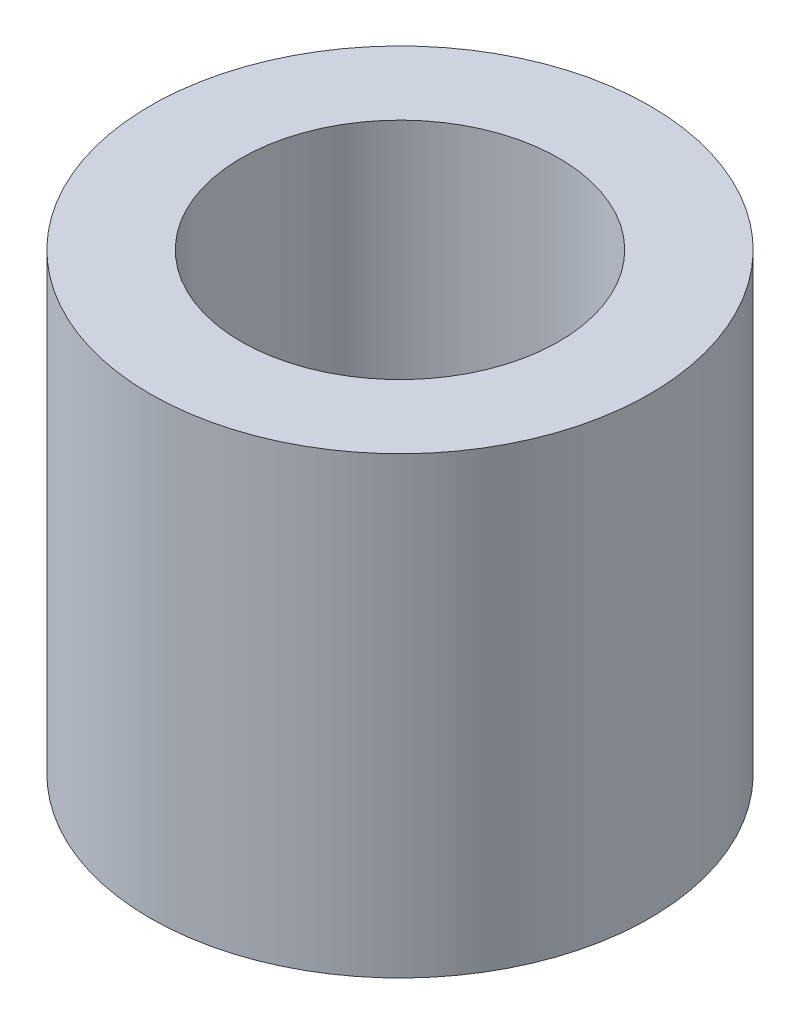
SolidWorks part; units mm, degrees
ref_plane "前视基准面" through (0, 0, 0) normal (0, 0, 1) x (1, 0, 0)
ref_plane "上视基准面" through (0, 0, 0) normal (0, 1, 0) x (1, 0, 0)
ref_plane "右视基准面" through (0, 0, 0) normal (1, 0, 0) x (0, 0, -1)
sketch "草图1" plane through (0, 0, 0) normal (0, 1, 0) x (1, 0, 0)
  circle A0 centre (0, 0) radius 1.75
  circle A1 centre (0, 0) radius 2.75
  dimension "D1" = 1
  dimension "D2" = 3.5
extrude "凸台-拉伸1" add sketch "草图1" along normal blind 5
